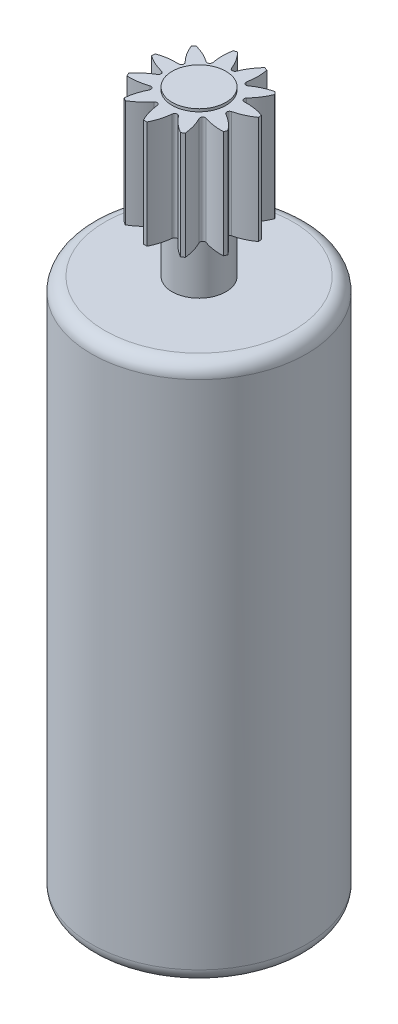
SolidWorks part; units mm, degrees
ref_plane "Front Plane" through (0, 0, 0) normal (0, 0, 1) x (1, 0, 0)
ref_plane "Top Plane" through (0, 0, 0) normal (0, 1, 0) x (1, 0, 0)
ref_plane "Right Plane" through (0, 0, 0) normal (1, 0, 0) x (0, 0, -1)
sketch "Sketch1" plane through (0, 0, 0) normal (0, 0, 1) x (1, 0, 0)
  line L0 (0, 0) -> (0, 26.1)
  line L1 (0, 0) -> (4, 0)
  line L2 (4, 0) -> (4, 20)
  line L3 (4, 20) -> (1, 20)
  line L4 (1, 20) -> (1, 22)
  line L5 (1, 22) -> (2, 22)
  line L6 (2, 22) -> (2, 26)
  line L7 (2, 26) -> (1, 26)
  line L8 (1, 26) -> (1, 26.1)
  line L9 (1, 26.1) -> (0, 26.1)
  dimension "D1" = 26.1
  dimension "D2" = 20
  dimension "D3" = 3
  dimension "D4" = 2
  dimension "D5" = 1
  dimension "D6" = 4
  dimension "D7" = 1
  dimension "D8" = 4
revolve "Revolve1" add sketch "Sketch1" angle 360 about L0
fillet "Fillet1" radius 0.5 2 edges at (0, 0, -4) (0, 20, -4)
sketch "Sketch2" plane through (0, 26, 0) normal (0, 1, 0) x (1, 0, 0)
  line L0 (0, 0) -> (0, 4) construction
  circle A0 centre (0, 0) radius 4 construction
  arc A1 (-0.5, 1.9365) -> (-0.0929, 1.2999) centre (-1.951, 0.5601) cw
  circle A2 centre (0, 0) radius 2 construction
  circle A3 centre (0, 0) radius 1 construction
  arc A4 (0.5, 1.9365) -> (0.0929, 1.2999) centre (1.951, 0.5601) ccw
  arc A5 (0.5, 1.9365) -> (-0.5, 1.9365) centre (0, 0) ccw
  arc A6 (-0.0929, 1.2999) -> (0.0929, 1.2999) centre (0, 1.3369) ccw
  point P16 (0, 1)
  dimension "D2" = 2
  dimension "D3" = 2
  dimension "D4" = 0.1
  dimension "D1" = 1
extrude "Cut-Extrude1" cut sketch "Sketch2" against normal blind 4
pattern_circular "CirPattern2" count 11 over 360 about axis through (0, 0, 0) along (0, 1, 0) of "Cut-Extrude1"
